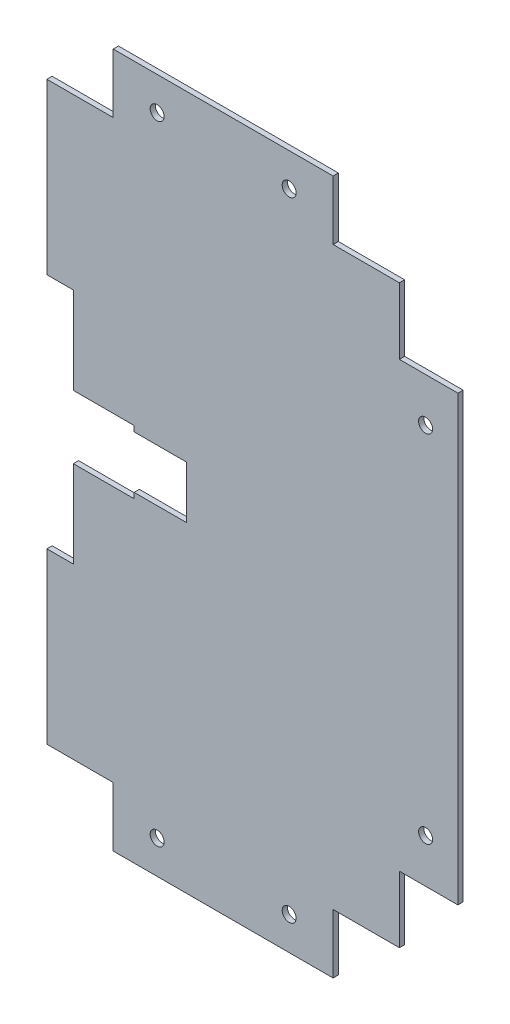
SolidWorks part; units mm, degrees
ref_plane "Front Plane" through (0, 0, 0) normal (0, 0, 1) x (1, 0, 0)
ref_plane "Top Plane" through (0, 0, 0) normal (0, 1, 0) x (1, 0, 0)
ref_plane "Right Plane" through (0, 0, 0) normal (1, 0, 0) x (0, 0, -1)
sketch "Sketch1" plane through (0, 0, 0) normal (0, 0, 1) x (1, 0, 0)
  line L0 (195.645, 0) -> (195.645, 34.005)
  line L1 (0, 0) -> (195.645, 0)
  line L2 (46.835, 196) -> (232.325, 196) construction
  line L3 (198.82, 37.18) -> (232.325, 37.18)
  line L4 (232.325, 37.18) -> (232.325, 360.81)
  line L7 (0, 0) -> (0, 34.005)
  line L8 (-3.175, 34.005) -> (-3.175, 145.99)
  line L9 (-3.175, 145.99) -> (12.005, 145.99)
  line L10 (46.835, 196) -> (46.835, 180.82)
  line L11 (46.835, 180.82) -> (12.005, 180.82)
  line L12 (12.005, 180.82) -> (12.005, 145.99)
  line L13 (-3.175, 34.005) -> (0, 34.005)
  line L14 (46.835, 198.995) -> (232.325, 198.995) construction
  line L15 (46.835, 196) -> (46.835, 201.99)
  line L16 (-3.175, 363.985) -> (0, 363.985)
  line L17 (12.005, 217.17) -> (12.005, 252)
  line L18 (46.835, 217.17) -> (12.005, 217.17)
  line L19 (46.835, 201.99) -> (46.835, 217.17)
  line L20 (-3.175, 252) -> (12.005, 252)
  line L21 (-3.175, 363.985) -> (-3.175, 252)
  line L22 (0, 397.99) -> (0, 363.985)
  line L23 (198.82, 360.81) -> (232.325, 360.81)
  line L24 (0, 397.99) -> (195.645, 397.99)
  line L25 (195.645, 397.99) -> (195.645, 363.985)
  line L26 (12.005, 266.995) -> (-3.175, 266.995)
  line L27 (198.82, 37.18) -> (232.325, 37.18)
  line L29 (198.82, 72.005) -> (232.325, 72.005)
  line L30 (232.325, 37.18) -> (232.325, 72.005)
  line L32 (195.645, 34.005) -> (195.645, 0)
  line L33 (195.645, 0) -> (160.82, 0)
  line L34 (160.82, 34.005) -> (160.82, 0)
  line L35 (0, 34.005) -> (34.825, 34.005)
  line L36 (0, 34.005) -> (0, 0)
  line L37 (0, 0) -> (34.825, 0)
  line L38 (34.825, 34.005) -> (34.825, 0)
  line L39 (12.005, 145.99) -> (-3.175, 145.99)
  line L40 (12.005, 145.99) -> (12.005, 130.995)
  line L41 (12.005, 130.995) -> (-3.175, 130.995)
  line L42 (-3.175, 145.99) -> (-3.175, 130.995)
  line L47 (-3.175, 252) -> (-3.175, 266.995)
  line L48 (12.005, 252) -> (-3.175, 252)
  line L49 (12.005, 252) -> (12.005, 266.995)
  line L50 (0, 397.99) -> (34.825, 397.99)
  line L51 (34.825, 363.985) -> (34.825, 397.99)
  line L52 (0, 363.985) -> (34.825, 363.985)
  line L53 (0, 363.985) -> (0, 397.99)
  line L54 (195.645, 397.99) -> (160.82, 397.99)
  line L55 (160.82, 363.985) -> (160.82, 397.99)
  line L56 (198.82, 72.005) -> (198.82, 34.005)
  line L57 (195.645, 363.985) -> (195.645, 397.99)
  line L58 (198.82, 325.985) -> (232.325, 325.985)
  line L59 (232.325, 360.81) -> (232.325, 325.985)
  line L60 (198.82, 360.81) -> (232.325, 360.81)
  line L61 (160.82, 34.005) -> (198.82, 34.005)
  line L62 (160.82, 363.985) -> (198.82, 363.985)
  line L63 (198.82, 325.985) -> (198.82, 363.985)
  line L65 (195.645, 34.005) -> (198.82, 34.005)
  line L68 (198.82, 34.005) -> (198.82, 37.18)
  line L69 (198.82, 363.985) -> (198.82, 360.81)
  line L70 (195.645, 363.985) -> (198.82, 363.985)
  line L71 (46.835, 183.995) -> (76.83, 183.995)
  line L72 (46.835, 183.995) -> (46.835, 213.995)
  line L75 (195.645, 363.985) -> (198.82, 363.985)
  line L76 (198.82, 360.81) -> (198.82, 363.985)
  line L77 (46.835, 213.995) -> (76.83, 213.995)
  line L78 (76.83, 183.995) -> (76.83, 213.995)
  circle A0 centre (135.645, 19.005) radius 4
  circle A1 centre (60, 19.005) radius 4
  circle A2 centre (213.82, 97.18) radius 4
  circle A3 centre (213.82, 300.81) radius 4
  circle A4 centre (60, 378.985) radius 4
  circle A5 centre (135.645, 378.985) radius 4
  dimension "D13" = 8
  dimension "D1" = 34.005
  dimension "D2" = 3.175
  dimension "D3" = 235.5
  dimension "D4" = 34.005
  dimension "D5" = 33.505
  dimension "D6" = 34.825
  dimension "D7" = 34.83
  dimension "D8" = 15.18
  dimension "D9" = 196
  dimension "D10" = 15.18
  dimension "D11" = 34.83
  dimension "D12" = 34.825
  dimension "D14" = 60
  dimension "D15" = 18.175
  dimension "D16" = 60
  dimension "D17" = 60
  dimension "D18" = 18.175
  dimension "D19" = 64.825
  dimension "D20" = 18.175
  dimension "D21" = 34.825
  dimension "D22" = 68
  dimension "D23" = 37.18
  dimension "D24" = 38
  dimension "D25" = 30
  dimension "D26" = 15
extrude "Boss-Extrude2" add sketch "Sketch1" along normal blind 3
